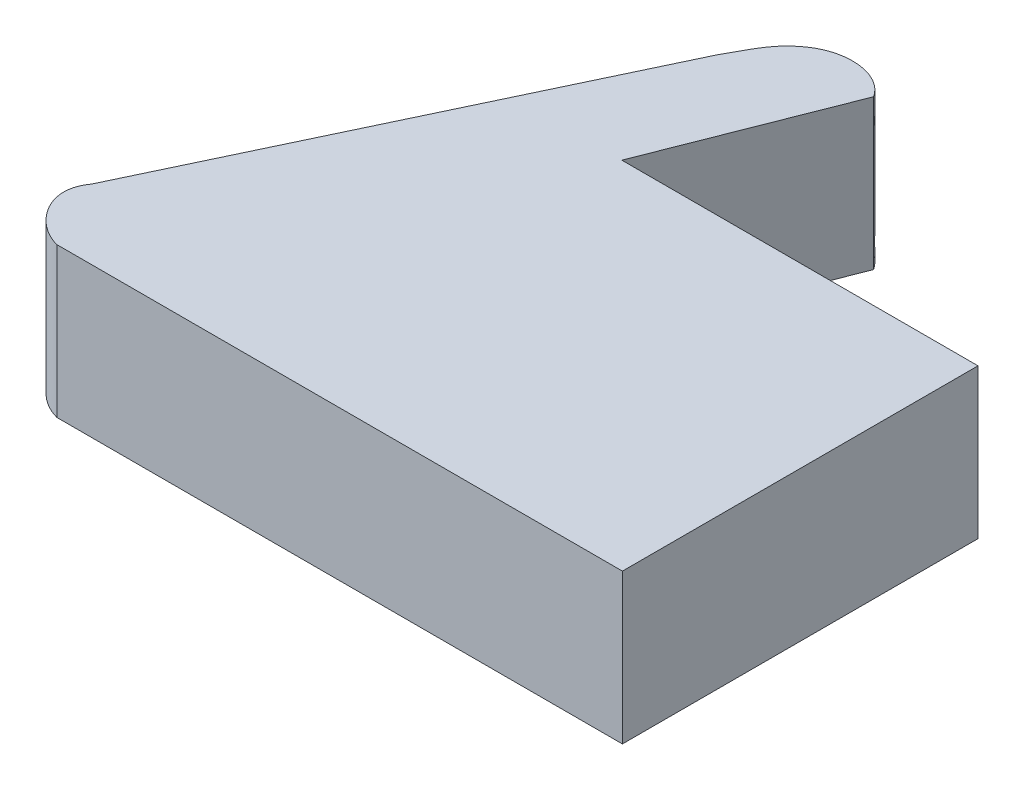
SolidWorks part; units mm, degrees
ref_plane "Front Plane" through (0, 0, 0) normal (0, 0, 1) x (1, 0, 0)
ref_plane "Top Plane" through (0, 0, 0) normal (0, 1, 0) x (1, 0, 0)
ref_plane "Right Plane" through (0, 0, 0) normal (1, 0, 0) x (0, 0, -1)
sketch "Sketch1" plane through (0, 0, 0) normal (0, 1, 0) x (1, 0, 0)
  line L0 (0, 0) -> (105.7604, 0)
  line L1 (105.7604, 0) -> (105.7604, 66.5058)
  line L2 (105.7604, 66.5058) -> (39.1465, 66.5058)
  line L3 (39.1465, 66.5058) -> (52.4157, 100.3239)
  line L4 (30.9726, 92.447) -> (-6.571, 13.0501)
  spline S0 degree 3 poles (52.4157, 100.3239) (50.0771, 103.9425) (41.8976, 105.5365) (34.2801, 99.2943) (32.2286, 94.5668) (30.9726, 92.447) knots 0 0 0 0 0.447116 0.733608 1 1 1 1
  spline S1 degree 3 poles (-6.571, 13.0501) (-10.4028, 7.9206) (-5.1855, 1.2855) (0, 0) knots 0 0 0 0 1 1 1 1
extrude "Boss-Extrude1" add sketch "Sketch1" along normal blind 28
